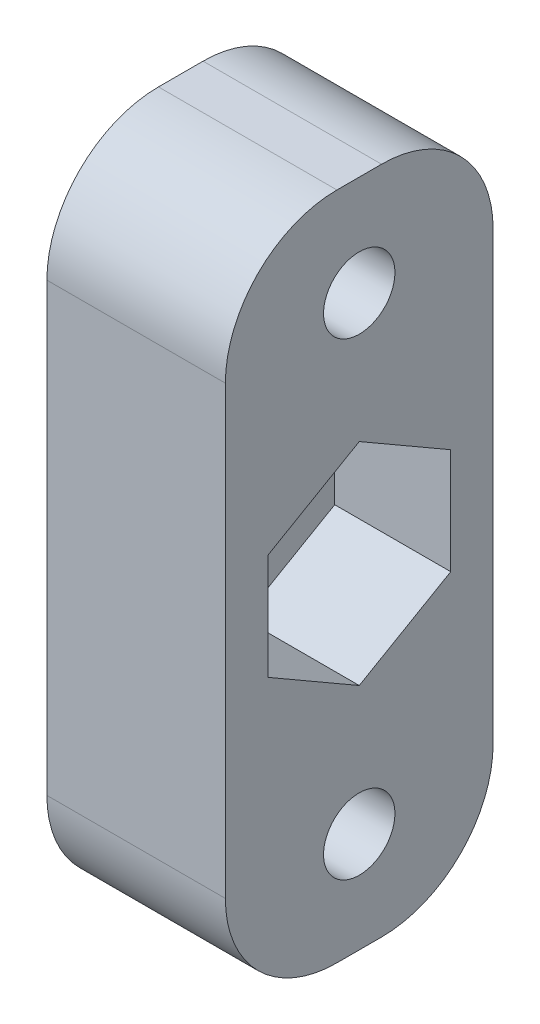
SolidWorks part; units mm, degrees
ref_plane "xy" through (0, 0, 0) normal (0, 0, 1) x (1, 0, 0)
ref_plane "xz" through (0, 0, 0) normal (0, 1, 0) x (1, 0, 0)
ref_plane "yz" through (0, 0, 0) normal (1, 0, 0) x (0, 0, -1)
sketch "Skizze1" plane through (0, 0, 0) normal (0, 0, 1) x (1, 0, 0)
  line L0 (-8, 15) -> (-8, -15)
  line L1 (-8, 15) -> (0, 15)
  line L2 (-8, 0) -> (0, 0) construction
  line L3 (-8, -15) -> (0, -15)
  line L4 (0, 15) -> (0, -15)
  line L5 (0, 6) -> (0, -6) construction
  line L6 (0, 6) -> (0, 15) construction
  line L7 (0, -6) -> (0, -15) construction
  point P9 (0, -10.5)
  point P12 (0, 10.5)
  dimension "D1" = 30
  dimension "D2" = 12
  dimension "D3" = 8
extrude "Aufsatz-Linear austragen1" add sketch "Skizze1" along normal mid plane 12
sketch "Skizze2" plane through (0, 0, 0) normal (1, 0, 0) x (0, 0, -1)
  line L1 (0, 4.7343) -> (-4.1, 2.3671)
  line L2 (-4.1, 2.3671) -> (-4.1, -2.3671)
  line L3 (-4.1, -2.3671) -> (0, -4.7343)
  line L4 (0, -4.7343) -> (4.1, -2.3671)
  line L5 (4.1, -2.3671) -> (4.1, 2.3671)
  line L6 (4.1, 2.3671) -> (0, 4.7343)
  circle A0 centre (0, 0) radius 4.1 construction
  dimension "D1" = 8.2
sketch "Skizze3" plane through (0, 0, 0) normal (1, 0, 0) x (0, 0, -1)
  line L1 (2.85, 8.8546) -> (2.85, 12.1454)
  line L2 (2.85, 12.1454) -> (0, 13.7909)
  line L3 (0, 13.7909) -> (-2.85, 12.1454)
  line L4 (-2.85, 12.1454) -> (-2.85, 8.8546)
  line L5 (-2.85, 8.8546) -> (0, 7.2091)
  line L6 (0, 7.2091) -> (2.85, 8.8546)
  circle A0 centre (0, 10.5) radius 2.85 construction
  dimension "D1" = 5.7
extrude "Schnitt-Linear austragen3" cut sketch "Skizze2" against normal blind 5.2
extrude "Schnitt-Linear austragen2" cut sketch "Skizze3" along normal blind 5.2 from surface at -8 starting at face at (-8, 0, 0)
sketch "Skizze4" plane through (0, 0, 0) normal (1, 0, 0) x (0, 0, -1)
  circle A0 centre (0, 10.5) radius 1.6
  circle A1 centre (0, -10.5) radius 1.6
  circle A2 centre (0, 0) radius 2.6
  dimension "D1" = 3.2
  dimension "D2" = 5.2
extrude "Schnitt-Linear austragen4" cut sketch "Skizze4" against normal through all
mirror "Spiegeln1" about plane through (0, 0, 0) normal (0, 1, 0) of "Schnitt-Linear austragen2"
fillet "Verrundung1" radius 5 4 edges at (-4, 15, 6) (-4, 15, -6) (-4, -15, 6) (-4, -15, -6)
